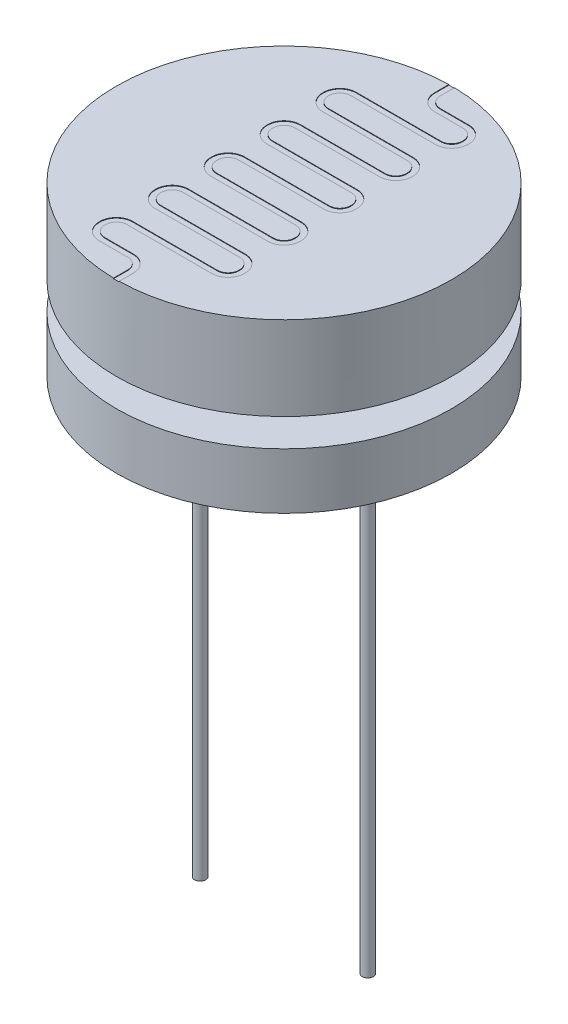
SolidWorks part; units mm, degrees
ref_plane "Front" through (0, 0, 0) normal (0, 0, 1) x (1, 0, 0)
ref_plane "Top" through (0, 0, 0) normal (0, 1, 0) x (1, 0, 0)
ref_plane "Right" through (0, 0, 0) normal (1, 0, 0) x (0, 0, -1)
sketch "Sketch1" plane through (0, 0, 0) normal (0, 1, 0) x (1, 0, 0)
  circle A0 centre (0, 0) radius 3
extrude "Boss-Extrude1" add sketch "Sketch1" along normal blind 3
sketch "Sketch2" plane through (0, 0, 0) normal (1, 0, 0) x (0, 0, -1)
  line L1 (-3, 1) -> (3, 1)
  line L2 (3, 0) -> (3, 3) construction
  line L3 (3, 1) -> (3, 1.5)
  line L4 (3, 0) -> (3, 3) construction
  line L5 (3, 1.5) -> (-3, 1.5)
  line L6 (-3, 3) -> (-3, 0) construction
  line L7 (-3, 1.5) -> (-3, 1)
extrude "Cut-Extrude1" cut sketch "Sketch2" against normal through all and the other way through all
sketch "Sketch3" plane through (0, 1.5, 0) normal (0, -1, 0) x (1, 0, 0)
  circle A1 centre (-1.5, 0) radius 0.1
  circle A2 centre (1.5, 0) radius 0.1
extrude "Boss-Extrude2" add sketch "Sketch3" along normal blind 10
sketch "Sketch4" plane through (0, 3, 0) normal (0, 1, 0) x (1, 0, 0)
  line L1 (-1, -0.2433) -> (-1, -0.2567)
  line L4 (1, -0.7433) -> (1, -0.7567)
  line L6 (-1, -1.2433) -> (-1, -1.2567)
  line L7 (1, 0.2433) -> (1, 0.2567)
  line L9 (1, -1.7433) -> (1, -1.7567)
  line L11 (-1, -2.2433) -> (-1, -2.2567)
  line L14 (-1, 0.7433) -> (-1, 0.7567)
  line L16 (1, 1.2433) -> (1, 1.2567)
  line L18 (-1, 1.7433) -> (-1, 1.7567)
  line L20 (1, 2.2433) -> (1, 2.2567)
  line L23 (0.05, -2.7433) -> (0.05, -3)
  line L24 (-0.7567, -2.45) -> (-0.2433, -2.45)
  line L25 (-0.95, -2.2433) -> (-0.95, -2.2567)
  line L26 (0.7567, -2.05) -> (-0.7567, -2.05)
  line L27 (1.05, -1.7433) -> (1.05, -1.7567)
  line L28 (-0.7567, -1.45) -> (0.7567, -1.45)
  line L29 (-0.95, -1.2433) -> (-0.95, -1.2567)
  line L30 (0.7567, -1.05) -> (-0.7567, -1.05)
  line L31 (1.05, -0.7433) -> (1.05, -0.7567)
  line L32 (-0.7567, -0.45) -> (0.7567, -0.45)
  line L33 (-0.95, -0.2433) -> (-0.95, -0.2567)
  line L34 (-0.7567, -0.05) -> (0.7567, -0.05)
  line L35 (1.05, 0.2433) -> (1.05, 0.2567)
  line L36 (-0.7567, 0.55) -> (0.7567, 0.55)
  line L37 (-0.95, 0.7433) -> (-0.95, 0.7567)
  line L38 (-0.7567, 0.95) -> (0.7567, 0.95)
  line L39 (1.05, 1.2433) -> (1.05, 1.2567)
  line L40 (0.7567, 1.55) -> (-0.7567, 1.55)
  line L41 (-0.95, 1.7433) -> (-0.95, 1.7567)
  line L42 (-0.7567, 1.95) -> (0.7567, 1.95)
  line L43 (1.05, 2.2433) -> (1.05, 2.2567)
  line L44 (0.7567, 2.55) -> (0.2433, 2.55)
  line L45 (0.05, 2.7433) -> (0.05, 3)
  line L46 (-0.05, -2.7433) -> (-0.05, -3)
  line L47 (-0.7567, -2.55) -> (-0.2433, -2.55)
  line L48 (-1.05, -2.2433) -> (-1.05, -2.2567)
  line L49 (0.7567, -1.95) -> (-0.7567, -1.95)
  line L50 (0.95, -1.7433) -> (0.95, -1.7567)
  line L51 (-0.7567, -1.55) -> (0.7567, -1.55)
  line L52 (-1.05, -1.2433) -> (-1.05, -1.2567)
  line L53 (0.7567, -0.95) -> (-0.7567, -0.95)
  line L54 (0.95, -0.7433) -> (0.95, -0.7567)
  line L55 (-0.7567, -0.55) -> (0.7567, -0.55)
  line L56 (-1.05, -0.2433) -> (-1.05, -0.2567)
  line L57 (-0.7567, 0.05) -> (0.7567, 0.05)
  line L58 (0.95, 0.2433) -> (0.95, 0.2567)
  line L59 (-0.7567, 0.45) -> (0.7567, 0.45)
  line L60 (-1.05, 0.7433) -> (-1.05, 0.7567)
  line L61 (-0.7567, 1.05) -> (0.7567, 1.05)
  line L62 (0.95, 1.2433) -> (0.95, 1.2567)
  line L63 (0.7567, 1.45) -> (-0.7567, 1.45)
  line L64 (-1.05, 1.7433) -> (-1.05, 1.7567)
  line L65 (-0.7567, 2.05) -> (0.7567, 2.05)
  line L66 (0.95, 2.2433) -> (0.95, 2.2567)
  line L67 (0.7567, 2.45) -> (0.2433, 2.45)
  line L68 (-0.05, 2.7433) -> (-0.05, 3)
  line L69 (0, 2.7433) -> (0, 3) construction
  line L70 (0.7567, 2.5) -> (0.2433, 2.5) construction
  line L71 (-0.7567, 2) -> (0.7567, 2) construction
  line L72 (0.7567, 1.5) -> (-0.7567, 1.5) construction
  line L73 (-0.7567, 1) -> (0.7567, 1) construction
  line L74 (-0.7567, 0.5) -> (0.7567, 0.5) construction
  line L75 (-0.7567, 0) -> (0.7567, 0) construction
  line L76 (-0.7567, -0.5) -> (0.7567, -0.5) construction
  line L77 (0.7567, -1) -> (-0.7567, -1) construction
  line L78 (-0.7567, -1.5) -> (0.7567, -1.5) construction
  line L79 (0.7567, -2) -> (-0.7567, -2) construction
  line L80 (-0.7567, -2.5) -> (-0.2433, -2.5) construction
  line L81 (0, -2.7433) -> (0, -3) construction
  arc A1 (-0.05, -3) -> (0.05, -3) centre (0, 0) ccw
  arc A2 (0.05, 3) -> (-0.05, 3) centre (0, 0) ccw
  arc A23 (0.05, -2.7433) -> (-0.2433, -2.45) centre (-0.2433, -2.7433) ccw
  arc A24 (-0.95, -2.2567) -> (-0.7567, -2.45) centre (-0.7567, -2.2567) ccw
  arc A25 (-0.95, -2.2433) -> (-0.7567, -2.05) centre (-0.7567, -2.2433) cw
  arc A26 (0.7567, -2.05) -> (1.05, -1.7567) centre (0.7567, -1.7567) ccw
  arc A27 (1.05, -1.7433) -> (0.7567, -1.45) centre (0.7567, -1.7433) ccw
  arc A28 (-0.95, -1.2567) -> (-0.7567, -1.45) centre (-0.7567, -1.2567) ccw
  arc A29 (-0.7567, -1.05) -> (-0.95, -1.2433) centre (-0.7567, -1.2433) ccw
  arc A30 (1.05, -0.7567) -> (0.7567, -1.05) centre (0.7567, -0.7567) cw
  arc A31 (1.05, -0.7433) -> (0.7567, -0.45) centre (0.7567, -0.7433) ccw
  arc A32 (-0.95, -0.2567) -> (-0.7567, -0.45) centre (-0.7567, -0.2567) ccw
  arc A33 (-0.7567, -0.05) -> (-0.95, -0.2433) centre (-0.7567, -0.2433) ccw
  arc A34 (1.05, 0.2433) -> (0.7567, -0.05) centre (0.7567, 0.2433) cw
  arc A35 (0.7567, 0.55) -> (1.05, 0.2567) centre (0.7567, 0.2567) cw
  arc A36 (-0.95, 0.7433) -> (-0.7567, 0.55) centre (-0.7567, 0.7433) ccw
  arc A37 (-0.95, 0.7567) -> (-0.7567, 0.95) centre (-0.7567, 0.7567) cw
  arc A38 (1.05, 1.2433) -> (0.7567, 0.95) centre (0.7567, 1.2433) cw
  arc A39 (1.05, 1.2567) -> (0.7567, 1.55) centre (0.7567, 1.2567) ccw
  arc A40 (-0.7567, 1.55) -> (-0.95, 1.7433) centre (-0.7567, 1.7433) cw
  arc A41 (-0.95, 1.7567) -> (-0.7567, 1.95) centre (-0.7567, 1.7567) cw
  arc A42 (0.7567, 1.95) -> (1.05, 2.2433) centre (0.7567, 2.2433) ccw
  arc A43 (1.05, 2.2567) -> (0.7567, 2.55) centre (0.7567, 2.2567) ccw
  arc A44 (0.2433, 2.55) -> (0.05, 2.7433) centre (0.2433, 2.7433) cw
  arc A45 (-0.05, -2.7433) -> (-0.2433, -2.55) centre (-0.2433, -2.7433) ccw
  arc A46 (-1.05, -2.2567) -> (-0.7567, -2.55) centre (-0.7567, -2.2567) ccw
  arc A47 (-1.05, -2.2433) -> (-0.7567, -1.95) centre (-0.7567, -2.2433) cw
  arc A48 (0.7567, -1.95) -> (0.95, -1.7567) centre (0.7567, -1.7567) ccw
  arc A49 (0.95, -1.7433) -> (0.7567, -1.55) centre (0.7567, -1.7433) ccw
  arc A50 (-1.05, -1.2567) -> (-0.7567, -1.55) centre (-0.7567, -1.2567) ccw
  arc A51 (-0.7567, -0.95) -> (-1.05, -1.2433) centre (-0.7567, -1.2433) ccw
  arc A52 (0.95, -0.7567) -> (0.7567, -0.95) centre (0.7567, -0.7567) cw
  arc A53 (0.95, -0.7433) -> (0.7567, -0.55) centre (0.7567, -0.7433) ccw
  arc A54 (-1.05, -0.2567) -> (-0.7567, -0.55) centre (-0.7567, -0.2567) ccw
  arc A55 (-0.7567, 0.05) -> (-1.05, -0.2433) centre (-0.7567, -0.2433) ccw
  arc A56 (0.95, 0.2433) -> (0.7567, 0.05) centre (0.7567, 0.2433) cw
  arc A57 (0.7567, 0.45) -> (0.95, 0.2567) centre (0.7567, 0.2567) cw
  arc A58 (-1.05, 0.7433) -> (-0.7567, 0.45) centre (-0.7567, 0.7433) ccw
  arc A59 (-1.05, 0.7567) -> (-0.7567, 1.05) centre (-0.7567, 0.7567) cw
  arc A60 (0.95, 1.2433) -> (0.7567, 1.05) centre (0.7567, 1.2433) cw
  arc A61 (0.95, 1.2567) -> (0.7567, 1.45) centre (0.7567, 1.2567) ccw
  arc A62 (-0.7567, 1.45) -> (-1.05, 1.7433) centre (-0.7567, 1.7433) cw
  arc A63 (-1.05, 1.7567) -> (-0.7567, 2.05) centre (-0.7567, 1.7567) cw
  arc A64 (0.7567, 2.05) -> (0.95, 2.2433) centre (0.7567, 2.2433) ccw
  arc A65 (0.95, 2.2567) -> (0.7567, 2.45) centre (0.7567, 2.2567) ccw
  arc A66 (0.2433, 2.45) -> (-0.05, 2.7433) centre (0.2433, 2.7433) cw
  arc A67 (0.2433, 2.5) -> (0, 2.7433) centre (0.2433, 2.7433) cw construction
  arc A68 (1, 2.2567) -> (0.7567, 2.5) centre (0.7567, 2.2567) ccw construction
  arc A69 (0.7567, 2) -> (1, 2.2433) centre (0.7567, 2.2433) ccw construction
  arc A70 (-1, 1.7567) -> (-0.7567, 2) centre (-0.7567, 1.7567) cw construction
  arc A71 (-0.7567, 1.5) -> (-1, 1.7433) centre (-0.7567, 1.7433) cw construction
  arc A72 (1, 1.2567) -> (0.7567, 1.5) centre (0.7567, 1.2567) ccw construction
  arc A73 (1, 1.2433) -> (0.7567, 1) centre (0.7567, 1.2433) cw construction
  arc A74 (-1, 0.7567) -> (-0.7567, 1) centre (-0.7567, 0.7567) cw construction
  arc A75 (-1, 0.7433) -> (-0.7567, 0.5) centre (-0.7567, 0.7433) ccw construction
  arc A76 (0.7567, 0.5) -> (1, 0.2567) centre (0.7567, 0.2567) cw construction
  arc A77 (1, 0.2433) -> (0.7567, 0) centre (0.7567, 0.2433) cw construction
  arc A78 (-0.7567, 0) -> (-1, -0.2433) centre (-0.7567, -0.2433) ccw construction
  arc A79 (-1, -0.2567) -> (-0.7567, -0.5) centre (-0.7567, -0.2567) ccw construction
  arc A80 (1, -0.7433) -> (0.7567, -0.5) centre (0.7567, -0.7433) ccw construction
  arc A81 (1, -0.7567) -> (0.7567, -1) centre (0.7567, -0.7567) cw construction
  arc A82 (-0.7567, -1) -> (-1, -1.2433) centre (-0.7567, -1.2433) ccw construction
  arc A83 (-1, -1.2567) -> (-0.7567, -1.5) centre (-0.7567, -1.2567) ccw construction
  arc A84 (1, -1.7433) -> (0.7567, -1.5) centre (0.7567, -1.7433) ccw construction
  arc A85 (0.7567, -2) -> (1, -1.7567) centre (0.7567, -1.7567) ccw construction
  arc A86 (-1, -2.2567) -> (-0.7567, -2.5) centre (-0.7567, -2.2567) ccw construction
  arc A87 (-1, -2.2433) -> (-0.7567, -2) centre (-0.7567, -2.2433) cw construction
  arc A88 (0, -2.7433) -> (-0.2433, -2.5) centre (-0.2433, -2.7433) ccw construction
  circle M1 centre (0, 0) radius 3
extrude "Cut-Extrude4" cut sketch "Sketch4" against normal blind 0.01 contours A66 L67 A65 L66 A64 L65 A63 L64 A62 L63 A61 L62 A60 L61 A59 L60 A58 L59 A57 L58 A56 L57 A55 L56 A54 L55 A53 L54 A52 L53 A51 L52 A50 L51 A49 L50 A48 L49 A47 L48 A46 L47 A45 L46 L23 A23 L24 A24 L25 A25 M1
scale "Scale1" scale about origin uniform scaling yes scale factor 0.5
